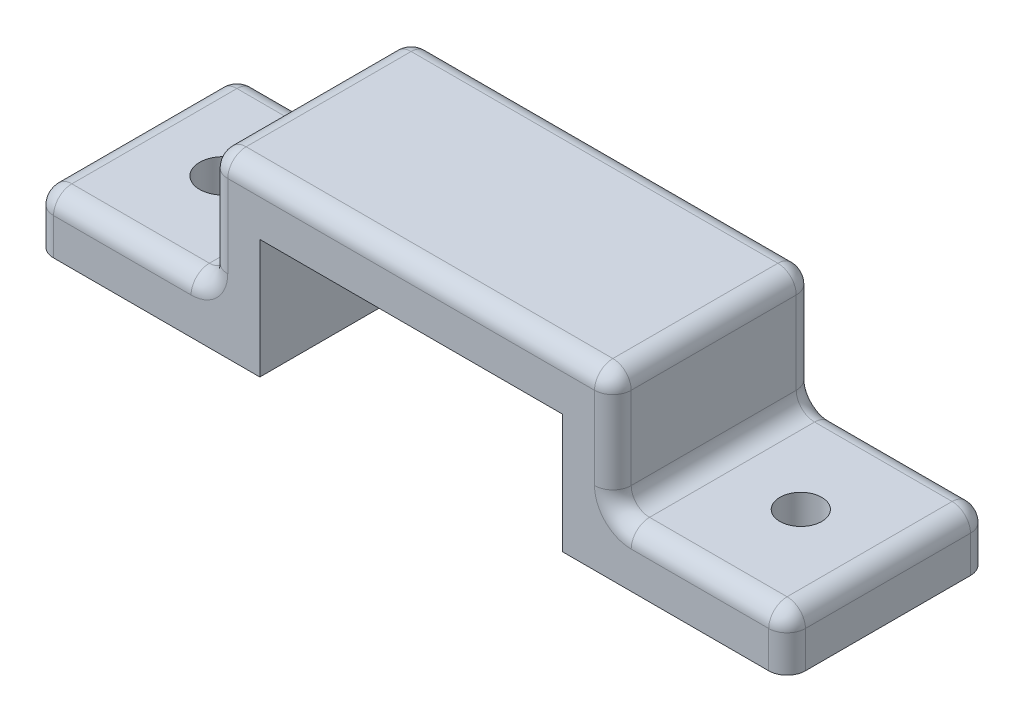
SolidWorks part; units mm, degrees
ref_plane "Front Plane" through (0, 0, 0) normal (0, 0, 1) x (1, 0, 0)
ref_plane "Top Plane" through (0, 0, 0) normal (0, 1, 0) x (1, 0, 0)
ref_plane "Right Plane" through (0, 0, 0) normal (1, 0, 0) x (0, 0, -1)
sketch "Sketch1" plane through (0, 0, 0) normal (0, 1, 0) x (1, 0, 0)
  line L0 (0, -13.97) -> (0, 13.97) construction
  line L1 (-52.07, -13.97) -> (52.07, -13.97)
  line L2 (-52.07, -13.97) -> (-52.07, 13.97)
  line L3 (-52.07, 13.97) -> (52.07, 13.97)
  line L4 (52.07, -13.97) -> (52.07, 13.97)
  line L5 (-52.07, -13.97) -> (52.07, 13.97) construction
  line L6 (-52.07, 13.97) -> (52.07, -13.97) construction
  circle A0 centre (40.005, 0) radius 2.902
  circle A1 centre (-40.005, 0) radius 3.2614
  point P0 (0, 0)
  point P10 (0, 0)
  point P11 (-52.07, 0)
  point P14 (0, 13.97)
  point P15 (0, 0)
  dimension "D3" = 80.01
  dimension "D4" = 6.5228
  dimension "D1" = 27.94
  dimension "D2" = 104.14
extrude "Boss-Extrude1" add sketch "Sketch1" along normal blind 24.13
sketch "Sketch2" plane through (0, 0, 0) normal (0, -1, 0) x (1, 0, 0)
  line L0 (-52.07, 13.97) -> (52.07, 13.97) construction
  line L1 (-20.955, -6.35) -> (20.955, -6.35)
  line L2 (-20.955, -6.35) -> (-20.955, 13.97)
  line L3 (-20.955, 13.97) -> (20.955, 13.97)
  line L4 (20.955, -6.35) -> (20.955, 13.97)
  point P6 (0, -6.35)
  dimension "D1" = 20.32
  dimension "D2" = 41.91
extrude "Cut-Extrude1" cut sketch "Sketch2" against normal blind 16.51
sketch "Sketch4" plane through (0, 24.13, 0) normal (0, 1, 0) x (1, 0, 0)
  line L1 (-52.07, -13.97) -> (-27.94, -13.97)
  line L2 (-52.07, -13.97) -> (-52.07, 13.97)
  line L3 (-52.07, 13.97) -> (-27.94, 13.97)
  line L4 (-27.94, -13.97) -> (-27.94, 13.97)
  line L5 (52.07, 13.97) -> (-52.07, 13.97) construction
  line L6 (0, 0) -> (0, 50000) construction
  line L7 (52.07, 13.97) -> (27.94, 13.97)
  line L8 (27.94, -13.97) -> (27.94, 13.97)
  line L9 (52.07, -13.97) -> (27.94, -13.97)
  line L10 (52.07, -13.97) -> (52.07, 13.97)
  point P8 (-40.005, 13.97)
  point P20 (-40.005, 0)
  point P21 (0, 0)
  dimension "D1" = 27.94
extrude "Cut-Extrude2" cut sketch "Sketch4" against normal blind 16.51
fillet "Fillet1" radius 2.54 23 edges at (40.005, 7.62, -13.97) (40.005, 7.62, 13.97) (-40.005, 7.62, 13.97) (-40.005, 7.62, -13.97) (27.94, 15.875, -13.97) (27.94, 7.62, 0) (27.94, 15.875, 13.97) (-27.94, 15.875, 13.97) (-27.94, 7.62, 0) (-27.94, 15.875, -13.97) (27.94, 24.13, 0) (0, 24.13, 13.97) (-27.94, 24.13, 0) (0, 24.13, -13.97) (0, 16.51, -6.35) (20.955, 8.255, -6.35) (-20.955, 8.255, -6.35) (-52.07, 3.81, -13.97) (-52.07, 7.62, 0) (-52.07, 3.81, 13.97) (52.07, 3.81, -13.97) (52.07, 3.81, 13.97) (52.07, 7.62, 0)
